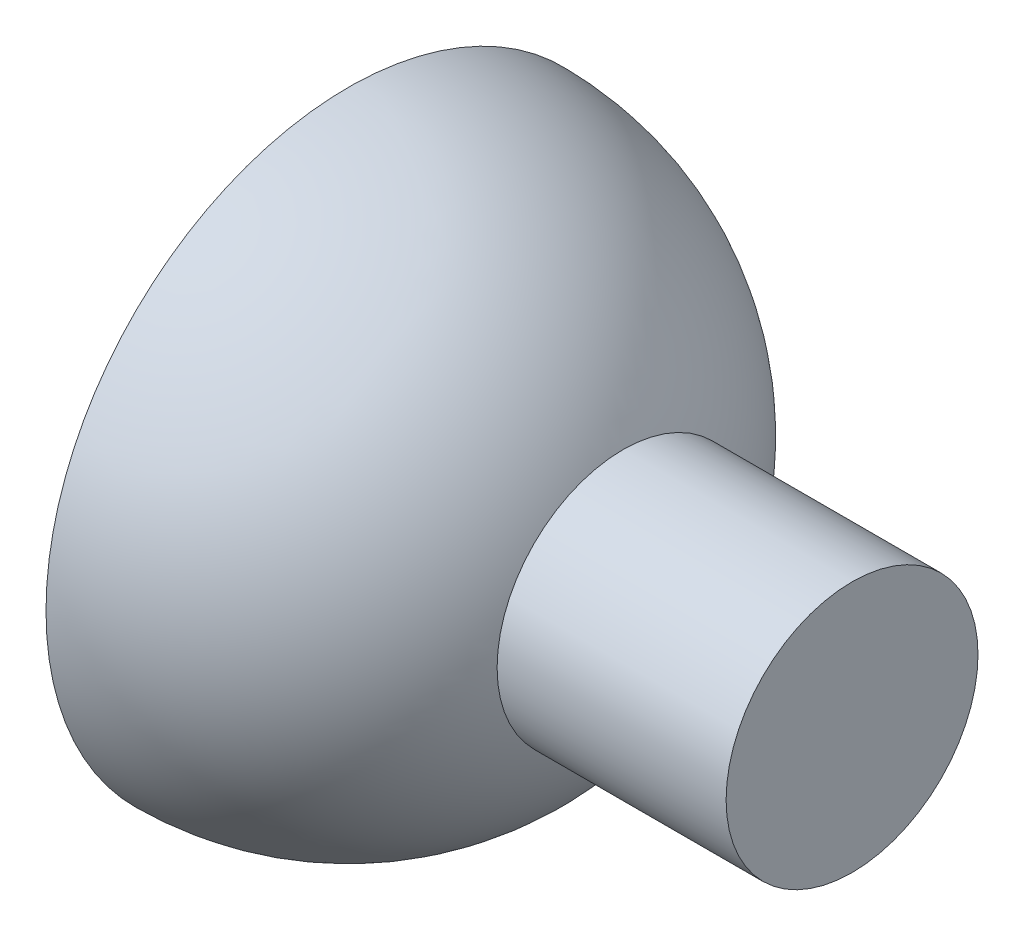
SolidWorks part; units mm, degrees
ref_plane "Front Plane" through (0, 0, 0) normal (0, 0, 1) x (1, 0, 0)
ref_plane "Top Plane" through (0, 0, 0) normal (0, 1, 0) x (1, 0, 0)
ref_plane "Right Plane" through (0, 0, 0) normal (1, 0, 0) x (0, 0, -1)
sketch "Sketch3" plane through (0, 0, 0) normal (0, 0, 1) x (1, 0, 0)
  line L2 (0, 0) -> (10, 0) construction
  arc A1 (10, 0) -> (0, 10) centre (0, 0) ccw
revolve "Revolve-Thin2" add sketch "Sketch3" angle 360 about L2
sketch "Sketch4" plane through (0, 0, 0) normal (-1, 0, 0) x (0, 0, 1)
  circle A0 centre (0, 0) radius 5
  dimension "D1" = 10
extrude "Boss-Extrude2" add sketch "Sketch4" against normal blind 5 and the other way up to surface from offset 15
